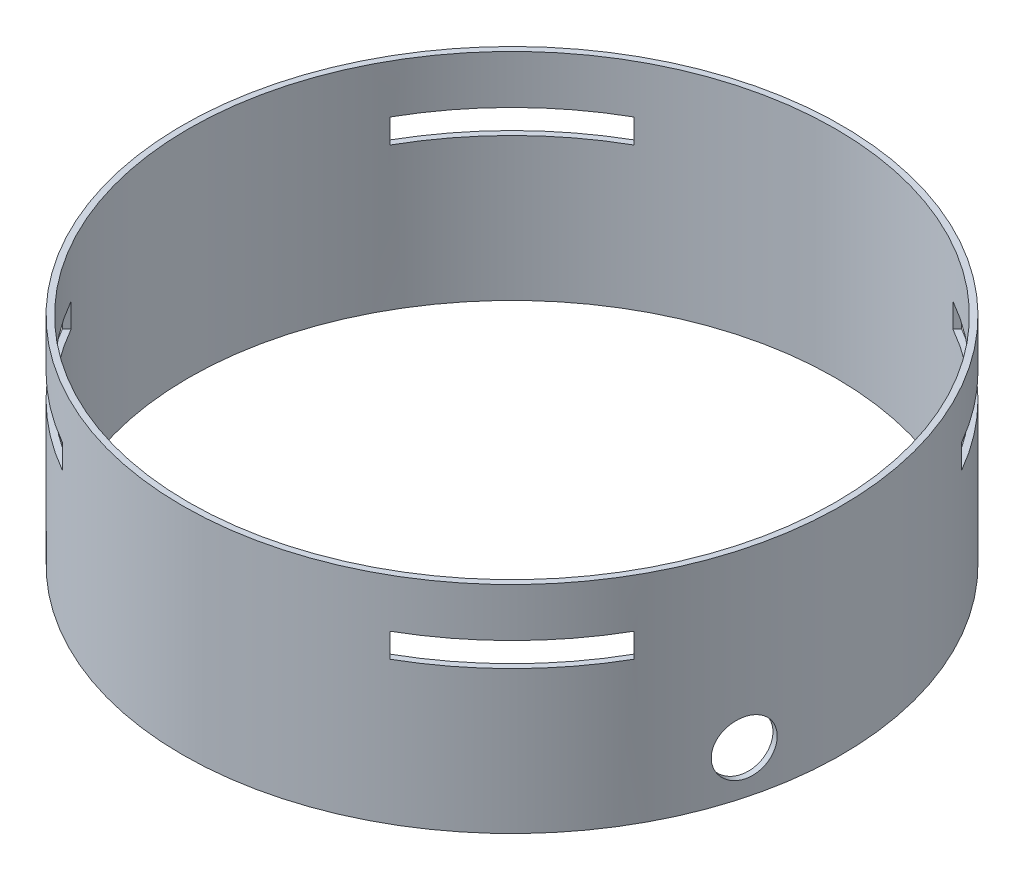
SolidWorks part; units mm, degrees
material "Thornel Mat VMA"
ref_plane "Front Plane" through (0, 0, 0) normal (0, 0, 1) x (1, 0, 0)
ref_plane "Top Plane" through (0, 0, 0) normal (0, 1, 0) x (1, 0, 0)
ref_plane "Right Plane" through (0, 0, 0) normal (1, 0, 0) x (0, 0, -1)
sketch "Sketch1" plane through (0, 0, 0) normal (0, 1, 0) x (1, 0, 0)
  circle A0 centre (0, 0) radius 76.2
  circle A1 centre (0, 0) radius 77.6224
  dimension "D1" = 152.4
  dimension "D2" = 155.2448
extrude "Boss-Extrude1" add sketch "Sketch1" along normal mid plane 50.8
ref_plane "Plane1" through (0, 0, 0) normal (-0.7071, 0, 0.7071) x (0.7071, 0, 0.7071)
sketch "Sketch2" plane through (0, 0, 0) normal (-0.7071, 0, 0.7071) x (0.7071, 0, 0.7071)
  line L0 (0, 0) -> (0, 11.1125) construction
  line L1 (76.2, 25.4) -> (-76.2, 25.4) construction
  line L2 (-20.32, 13.97) -> (20.32, 13.97)
  line L3 (-20.32, 13.97) -> (-20.32, 8.255)
  line L4 (-20.32, 8.255) -> (20.32, 8.255)
  line L5 (20.32, 13.97) -> (20.32, 8.255)
  line L6 (-20.32, 13.97) -> (20.32, 8.255) construction
  line L7 (-20.32, 8.255) -> (20.32, 13.97) construction
  dimension "D1" = 40.64
  dimension "D2" = 5.715
  dimension "D3" = 11.43
extrude "Cut-Extrude1" cut sketch "Sketch2" against normal through all
pattern_circular "CirPattern1" count 4 over 360 about axis through (0, 0, 0) along (0, 1, 0) of "Cut-Extrude1"
ref_plane "Plane2" through (74.9775, 0, 20.0902) normal (0.9659, 0, 0.2588) x (0, -1, 0)
sketch "Sketch3" plane through (74.9775, 0, 20.0902) normal (0.9659, 0, 0.2588) x (0, -1, 0)
  line L0 (0, 0) -> (25.4, 0) construction
  line L1 (25.4, -77.6224) -> (25.4, 77.6224) construction
  circle A0 centre (15.24, 0) radius 6.35
  dimension "D1" = 12.7
  dimension "D2" = 10.16
extrude "Cut-Extrude2" cut sketch "Sketch3" against normal blind 6.35
equation "\"airframeInnerDiameter\"= 6in"
equation "\"outerDiameter\"= 6.112in"
equation "\"atsLength\"= 11in"
equation "\"atsInner\"= 5.888in"
equation "\"atsBand\"= 2in"
equation "\"atsCouplerOuter\"=\"airframeInnerDiameter\""
equation "\"atsOffsetFromAft\"= 3in"
equation "\"D1@Sketch1\"=\"airframeInnerDiameter\""
equation "\"D2@Sketch1\"=\"outerDiameter\""
equation "\"D1@Boss-Extrude1\"=\"atsBand\""
equation "\"D1@Sketch3\"=0.5"
